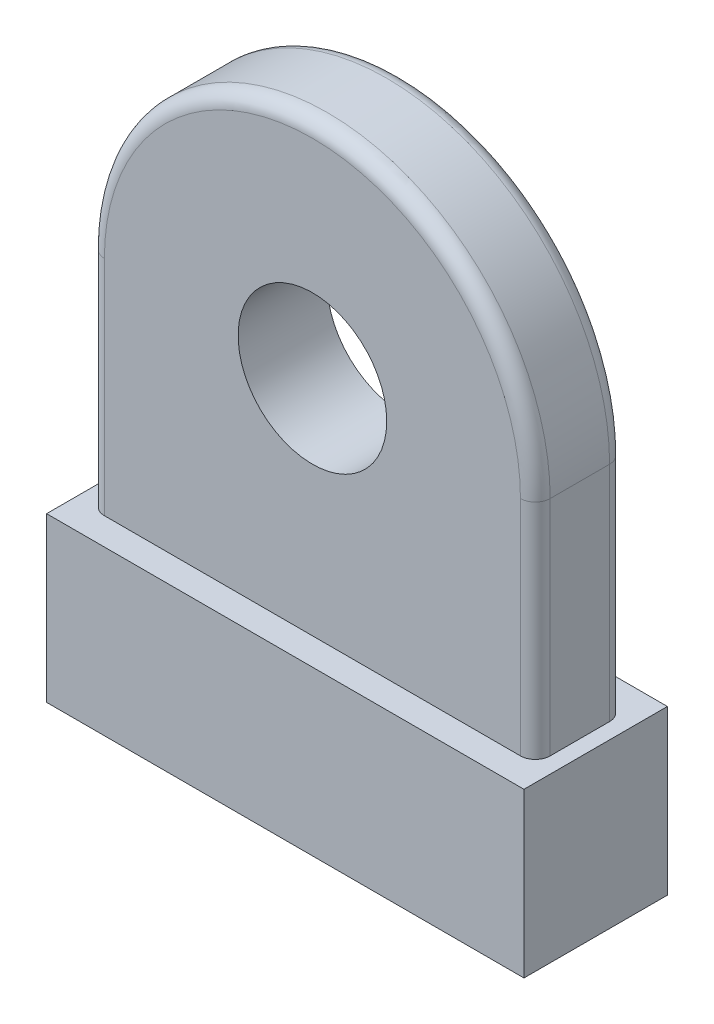
SolidWorks part; units mm, degrees
ref_plane "Front Plane" through (0, 0, 0) normal (0, 0, 1) x (1, 0, 0)
ref_plane "Top Plane" through (0, 0, 0) normal (0, 1, 0) x (1, 0, 0)
ref_plane "Right Plane" through (0, 0, 0) normal (1, 0, 0) x (0, 0, -1)
sketch "Sketch1" plane through (0, 0, 0) normal (0, 0, 1) x (1, 0, 0)
  line L0 (-15, 0) -> (-15, -15)
  line L1 (-15, -15) -> (15, -15)
  line L2 (15, -15) -> (15, 0)
  circle A0 centre (0, 0) radius 5
  arc A1 (15, 0) -> (-15, 0) centre (0, 0) ccw
  circle A2 centre (0, 0) radius 15 construction
  point P7 (0, 0)
  dimension "D2" = 10
  dimension "D3" = 15
  dimension "D1" = 10
extrude "Boss-Extrude1" add sketch "Sketch1" along normal blind 6
fillet "Fillet1" radius 1 6 edges at (15, -7.5, 0) (-15, -7.5, 0) (15, -7.5, 6) (-15, -7.5, 6) (0, 15, 0) (0, 15, 6)
sketch "Sketch2" plane through (0, -15, 0) normal (0, -1, 0) x (1, 0, 0)
  line L0 (-14, 6) -> (14, 6) construction
  line L1 (-16.0627, -1.8262) -> (16.0627, -1.8262)
  line L2 (-16.0627, -1.8262) -> (-16.0627, 7.8262)
  line L3 (-16.0627, 7.8262) -> (16.0627, 7.8262)
  line L4 (16.0627, -1.8262) -> (16.0627, 7.8262)
  line L5 (-15, 5) -> (-15, 1) construction
  point P6 (0, 6)
  point P7 (-15, 3)
  point P8 (0, 6)
  point P9 (0, 7.8262)
  point P10 (-16.0627, 3)
  point P11 (16.0627, -1.8262)
  point P13 (-15, 3)
extrude "Boss-Extrude2" add sketch "Sketch2" along normal blind 11 contours L3 L4 L1 L2
